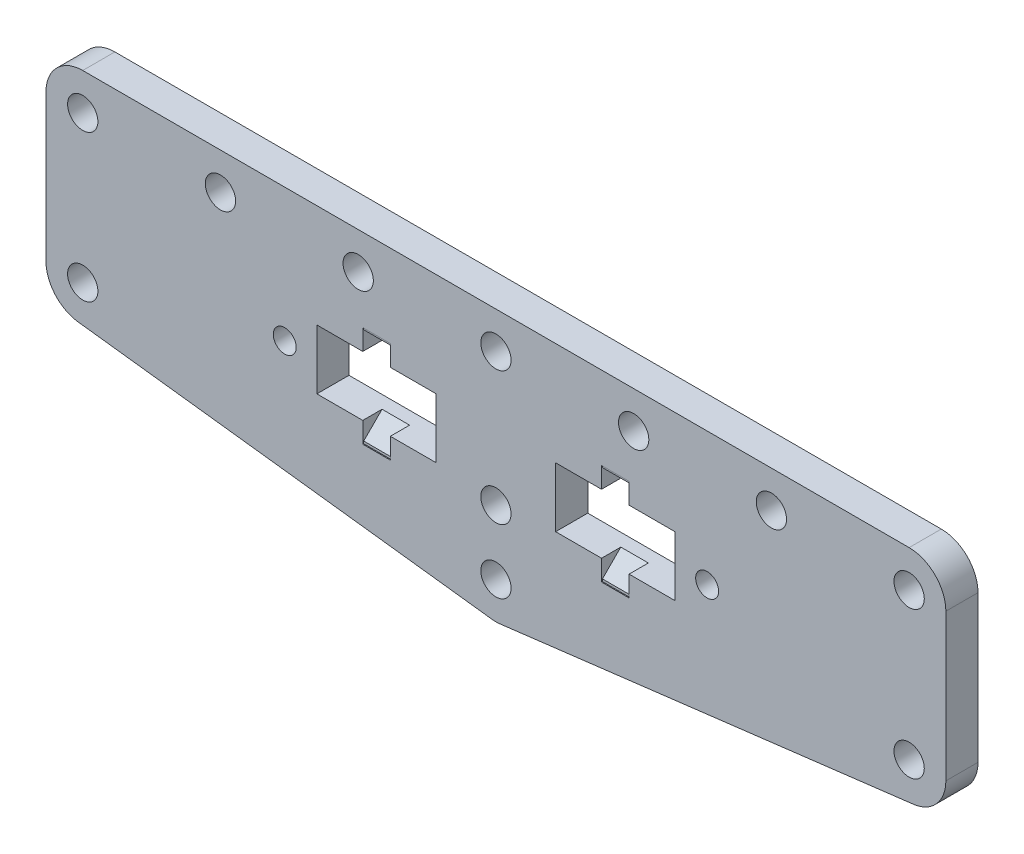
SolidWorks part; units mm, degrees
ref_plane "Płaszczyzna przednia" through (0, 0, 0) normal (0, 0, 1) x (1, 0, 0)
ref_plane "Płaszczyzna górna" through (0, 0, 0) normal (0, 1, 0) x (1, 0, 0)
ref_plane "Płaszczyzna prawa" through (0, 0, 0) normal (1, 0, 0) x (0, 0, -1)
sketch "Szkic1" plane through (0, 0, 0) normal (0, 0, 1) x (1, 0, 0)
  line L0 (0, 0) -> (60.5866, 0) construction
  line L1 (0.4853, -10.9705) -> (45.4853, -5.4705)
  line L2 (49, -1.5) -> (49, 14.5)
  line L3 (45, 18.5) -> (-45, 18.5)
  line L4 (0, 25.8414) -> (0, -26.3345) construction
  line L5 (-0.4853, -10.9705) -> (-45.4853, -5.4705)
  line L6 (-49, -1.5) -> (-49, 14.5)
  circle A0 centre (0, 0) radius 1.65
  circle A1 centre (0, -7) radius 1.65
  circle A2 centre (45, -1.5) radius 1.65
  circle A3 centre (45, 14.5) radius 1.65
  arc A4 (-0.4853, -10.9705) -> (0.4853, -10.9705) centre (0, -7) ccw
  arc A5 (45.4853, -5.4705) -> (48.7081, 0) centre (45, -1.5) ccw
  arc A6 (49, 14.5) -> (45, 18.5) centre (45, 14.5) ccw
  circle A7 centre (-45, -1.5) radius 1.65
  arc A8 (-45.4853, -5.4705) -> (-49, -1.5) centre (-45, -1.5) cw
  circle A9 centre (-45, 14.5) radius 1.65
  arc A10 (-49, 14.5) -> (-45, 18.5) centre (-45, 14.5) cw
  point P32 (0, 18.5)
  dimension "D1" = 3.3
  dimension "D2" = 3.3
  dimension "D5" = 3.3
  dimension "D7" = 3.3
  dimension "D9" = 8
  dimension "D10" = 8
  dimension "D3" = 7
  dimension "D4" = 1.5
  dimension "D6" = 45
  dimension "D8" = 16
extrude "Dodanie-wyciągnięcie1" add sketch "Szkic1" along normal blind 3.5
sketch "Szkic2" plane through (0, 0, 3.5) normal (0, 0, 1) x (1, 0, 0)
  line L1 (6.5, 7.25) -> (19.5, 7.25)
  line L2 (6.5, 7.25) -> (6.5, 0.75)
  line L3 (6.5, 0.75) -> (19.5, 0.75)
  line L4 (19.5, 7.25) -> (19.5, 0.75)
  line L5 (6.5, 7.25) -> (19.5, 0.75) construction
  line L6 (6.5, 0.75) -> (19.5, 7.25) construction
  point P0 (13, 4)
  dimension "D1" = 13
  dimension "D2" = 13
  dimension "D3" = 6.5
  dimension "D4" = 4
extrude "Wytnij-wyciągnięcie1" cut sketch "Szkic2" against normal blind 4
sketch "Szkic3" plane through (0, 0, 3.5) normal (0, 0, 1) x (1, 0, 0)
  line L0 (19.5, 4) -> (28.4602, 4) construction
  line L1 (19.5, 0.75) -> (19.5, 7.25) construction
  line L2 (19.5, 7.25) -> (6.5, 7.25) construction
  circle A0 centre (23, 4) radius 1.25
  point P8 (13, 7.25)
  dimension "D1" = 2.5
  dimension "D2" = 10
extrude "Wytnij-wyciągnięcie2" cut sketch "Szkic3" against normal blind 4
mirror "Lustro1" about plane through (0, 0, 0) normal (1, 0, 0) of "Wytnij-wyciągnięcie1", "Wytnij-wyciągnięcie2"
sketch "Szkic4" plane through (0, 0, 3.5) normal (0, 0, 1) x (1, 0, 0)
  line L0 (-45, 14.5) -> (45, 14.5) construction
  circle A0 centre (0, 14.5) radius 1.65
  circle A1 centre (15, 14.5) radius 1.65
  circle A2 centre (30, 14.5) radius 1.65
  dimension "D1" = 3.3
  dimension "D2" = 3.3
  dimension "D3" = 3.3
  dimension "D4" = 15
  dimension "D5" = 15
extrude "Wytnij-wyciągnięcie3" cut sketch "Szkic4" against normal blind 4
mirror "Lustro2" about plane through (0, 0, 0) normal (1, 0, 0) of "Wytnij-wyciągnięcie3"
sketch "Szkic5" plane through (0, 0, 3.5) normal (0, 0, 1) x (1, 0, 0)
  line L0 (6.5, 4) -> (19.5, 4) construction
  line L1 (6.5, 7.25) -> (6.5, 0.75) construction
  line L2 (19.5, 0.75) -> (19.5, 7.25) construction
  line L3 (13, 7.25) -> (13, 0.75) construction
  line L4 (19.5, 7.25) -> (6.5, 7.25) construction
  line L5 (6.5, 0.75) -> (19.5, 0.75) construction
  line L7 (11.5, 9.5) -> (14.5, 9.5)
  line L8 (11.5, 9.5) -> (11.5, -1.5)
  line L9 (11.5, -1.5) -> (14.5, -1.5)
  line L10 (14.5, 9.5) -> (14.5, -1.5)
  line L11 (11.5, 9.5) -> (14.5, -1.5) construction
  line L12 (11.5, -1.5) -> (14.5, 9.5) construction
  point P12 (13, 4)
  dimension "D1" = 3
  dimension "D2" = 11
extrude "Wytnij-wyciągnięcie4" cut sketch "Szkic5" against normal blind 0.1
chamfer "Sfazowanie1" distance 2 angle 45 2 edges at (13, 0.75, 3.4) (13, 7.25, 3.4)
mirror "Lustro6" about plane through (0, 0, 0) normal (1, 0, 0) of "Wytnij-wyciągnięcie4"
chamfer "Sfazowanie2" distance 2 angle 45 2 edges at (-13, 0.75, 3.4) (-13, 7.25, 3.4)
